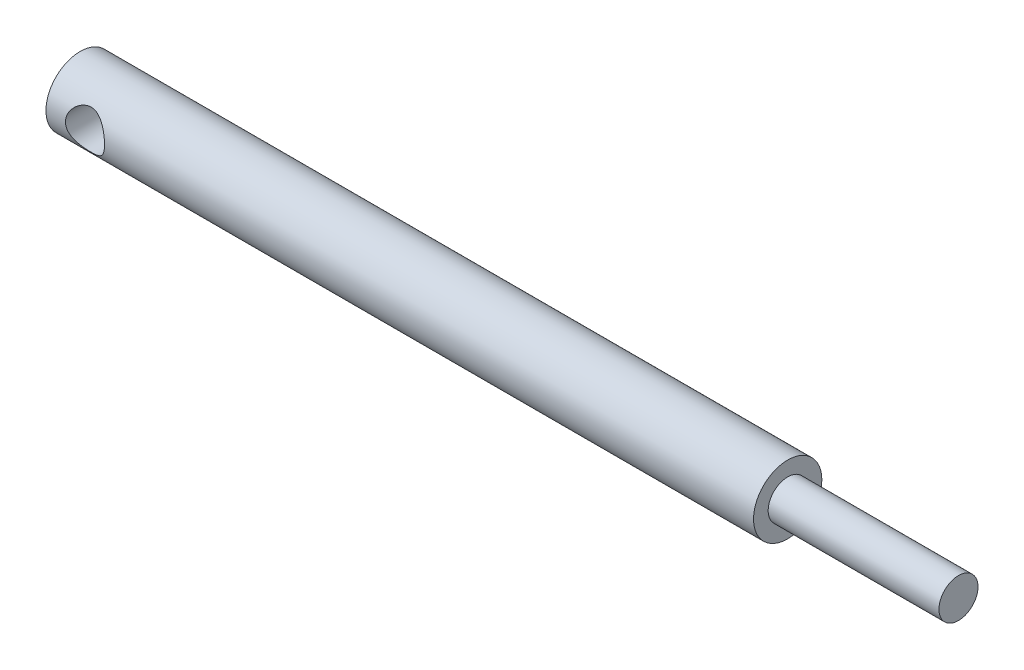
SolidWorks part; units mm, degrees
ref_plane "前视基准面" through (0, 0, 0) normal (0, 0, 1) x (1, 0, 0)
ref_plane "上视基准面" through (0, 0, 0) normal (0, 1, 0) x (1, 0, 0)
ref_plane "右视基准面" through (0, 0, 0) normal (1, 0, 0) x (0, 0, -1)
sketch "草图1" plane through (0, 0, 0) normal (0, 0, 1) x (1, 0, 0)
  line L0 (0, 7) -> (0, 0)
  line L1 (0, 0) -> (180, 0)
  line L2 (180, 0) -> (180, 4)
  line L3 (180, 4) -> (145, 4)
  line L4 (145, 4) -> (145, 7)
  line L5 (145, 7) -> (0, 7)
  line L6 (0, 0) -> (180, 0) construction
  line L7 (-268.9555, 0) -> (-50.7334, 0) construction
  dimension "D1" = 180
  dimension "D2" = 35
  dimension "D3" = 8
  dimension "D4" = 14
revolve "旋转1" add sketch "草图1" angle 360 about L6
sketch "草图3" plane through (0, 0, 0) normal (0, 0, 1) x (1, 0, 0)
  line L0 (0, 0) -> (146.057, 0) construction
  line L1 (0, 7) -> (0, -7) construction
  circle A0 centre (8, 0) radius 4
  dimension "D1" = 8
  dimension "D2" = 8
extrude "切除-拉伸1" cut sketch "草图3" against normal through all and the other way through all
